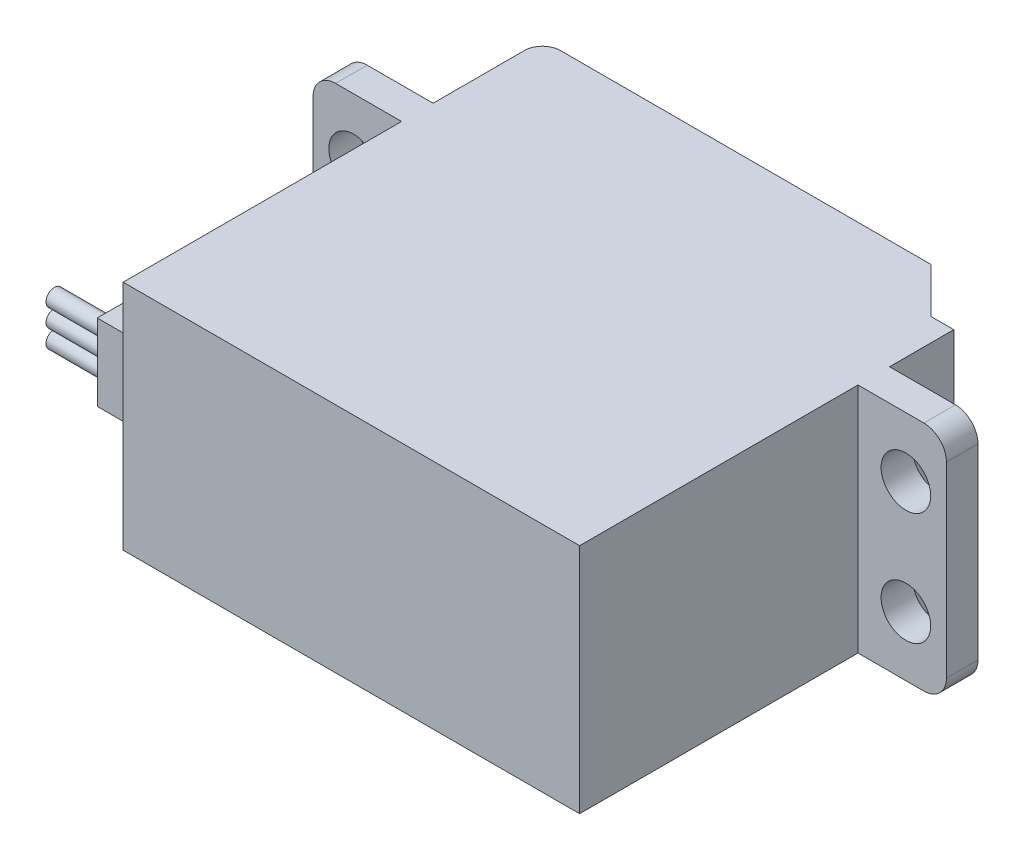
SolidWorks part; units mm, degrees
ref_plane "Plan de face" through (0, 0, 0) normal (0, 0, 1) x (1, 0, 0)
ref_plane "Plan de dessus" through (0, 0, 0) normal (0, 1, 0) x (1, 0, 0)
ref_plane "Plan de droite" through (0, 0, 0) normal (1, 0, 0) x (0, 0, -1)
sketch "Esquisse1" plane through (0, 0, 0) normal (0, 1, 0) x (1, 0, 0)
  line L0 (0, 0) -> (0, 12.5) construction
  line L5 (-20.25, 12.5) -> (14.25, 12.5)
  line L7 (20.25, 8.5) -> (20.25, -24.7)
  line L8 (20.25, -24.7) -> (-20.25, -24.7)
  line L9 (-20.25, 12.5) -> (-20.25, -24.7)
  line L11 (20.25, 8.5) -> (18.25, 8.5)
  line L12 (18.25, 8.5) -> (14.25, 12.5)
  point P9 (0, -24.7)
  dimension "D1" = 40.5
  dimension "D2" = 37.2
  dimension "D3" = 4
  dimension "D4" = 4
  dimension "D5" = 24.7
  dimension "D6" = 2
extrude "Boss.-Extru.1" add sketch "Esquisse1" along normal mid plane 20.6
sketch "Esquisse3" plane through (0, 0, 0) normal (0, 0, 1) x (1, 0, 0)
  line L1 (0, 0) -> (20.25, 0) construction
  line L3 (0, 0) -> (0, 10.3) construction
  line L16 (20.25, 10.3) -> (28.1, 10.3)
  line L17 (28.1, 10.3) -> (28.1, -10.3)
  line L18 (-20.25, 10.3) -> (-28.1, 10.3)
  line L19 (-28.1, 10.3) -> (-28.1, -10.3)
  line L20 (20.25, 10.3) -> (20.25, -10.3)
  line L21 (20.25, -10.3) -> (28.1, -10.3)
  line L22 (-20.25, -10.3) -> (-28.1, -10.3)
  line L23 (-20.25, 10.3) -> (-20.25, -10.3)
  line L24 (-20.25, 10.3) -> (20.25, 10.3) construction
  circle A4 centre (24.5, 5) radius 2.2
  circle A5 centre (24.5, -5) radius 2.2
  circle A8 centre (-24.5, 5) radius 2.2
  circle A9 centre (-24.5, -5) radius 2.2
  point P25 (28.1, 0)
  dimension "D4" = 4.4
  dimension "D1" = 10
  dimension "D2" = 49
  dimension "D3" = 56.2
extrude "Boss.-Extru.2" add sketch "Esquisse3" against normal blind 2.8
sketch "Esquisse4" plane through (0, 0, 0) normal (0, 1, 0) x (1, 0, 0)
  line L0 (20.25, 2.8) -> (20.25, 3.8)
  line L1 (20.25, 2.8) -> (20.25, 8.5) construction
  line L4 (23.75, 2.8) -> (20.25, 2.8)
  line L5 (0, 0) -> (0, 11.6297) construction
  line L9 (28.1, 2.8) -> (20.25, 2.8) construction
  line L10 (23.75, 2.8) -> (20.25, 3.8)
  line L16 (-23.75, 2.8) -> (-20.25, 3.8)
  line L17 (-23.75, 2.8) -> (-20.25, 2.8)
  line L18 (-20.25, 2.8) -> (-20.25, 3.8)
  dimension "D1" = 3.5
  dimension "D2" = 1
extrude "Boss.-Extru.3" add sketch "Esquisse4" along normal mid plane 1.2
sketch "Esquisse8" plane through (0, 0, -12.5) normal (0, 0, -1) x (-1, 0, 0)
  line L0 (0, 0) -> (10.25, 0) construction
  line L1 (20.25, -10.3) -> (20.25, -0.6) construction
  circle A0 centre (10.25, 0) radius 6.1
  dimension "D1" = 12.2
  dimension "D2" = 10
extrude "Boss.-Extru.7" add sketch "Esquisse8" along normal blind 0.5
sketch "Esquisse5" plane through (0, 0, -13) normal (0, 0, -1) x (-1, 0, 0)
  line L0 (0, 0) -> (10, 0) construction
  circle A0 centre (10, 0) radius 2.925
  dimension "D1" = 5.85
extrude "Boss.-Extru.4" add sketch "Esquisse5" along normal blind 3.9
fillet "Congé1" radius 2 4 edges at (-28.1, 10.3, -1.4) (-28.1, -10.3, -1.4) (28.1, 10.3, -1.4) (28.1, -10.3, -1.4)
sketch "Esquisse6" plane through (-20.25, 0, 0) normal (-1, 0, 0) x (0, 0, 1)
  line L0 (18.7, 0) -> (0, 0) construction
  line L1 (18.7, 3.4) -> (21.7, 3.4)
  line L2 (18.7, 3.4) -> (18.7, -3.4)
  line L3 (18.7, -3.4) -> (21.7, -3.4)
  line L4 (21.7, 3.4) -> (21.7, -3.4)
  line L5 (24.7, 10.3) -> (24.7, -10.3) construction
  point P7 (20.2, -3.4)
  dimension "D1" = 6.8
  dimension "D2" = 3
  dimension "D3" = 4.5
extrude "Boss.-Extru.5" add sketch "Esquisse6" along normal blind 5.3
sketch "Esquisse7" plane through (-25.55, 0, 0) normal (-1, 0, 0) x (0, 0, 1)
  line L0 (20.2, 3.4) -> (20.2, -3.4) construction
  line L1 (21.7, 3.4) -> (18.7, 3.4) construction
  line L2 (18.7, -3.4) -> (21.7, -3.4) construction
  line L3 (20.2, 0) -> (21.7, 0) construction
  line L4 (21.7, -3.4) -> (21.7, 3.4) construction
  circle A0 centre (20.2, 0) radius 0.75
  circle A1 centre (20.2, 1.6) radius 0.75
  circle A2 centre (20.2, -1.6) radius 0.75
  dimension "D1" = 1.5
  dimension "D2" = 1.6
extrude "Boss.-Extru.6" add sketch "Esquisse7" along normal blind 5.3
hole_wizard "Dégagement M31" positions "Esquisse10" profile "Esquisse12" hole size "M3" standard "ISO"
sketch "Esquisse10" plane through (0, 0, -16.9) normal (0, 0, -1) x (-1, 0, 0)
  point P0 (10, 0)
sketch "Esquisse12" plane through (-10, 0, -16.9) normal (1, 0, 0) x (0, 1, 0)
  line L0 (0, 0) -> (0, 6.9614)
  line L1 (0, 6.9614) -> (1.6, 6)
  line L2 (1.6, 6) -> (1.6, 0)
  line L5 (1.6, 0) -> (0, 0)
  line L10 (0, 6.9614) -> (-1.6, 6) construction
  line L11 (0, -6.35) -> (0, 107.95) construction
  dimension "Diamètre du perçage" = 3.2
  dimension "Profondeur du perçage" = 6
  dimension "Angle de pointe" = 118
fillet "Congé2" radius 1.6 1 edges at (-20.25, 0, -12.5)
